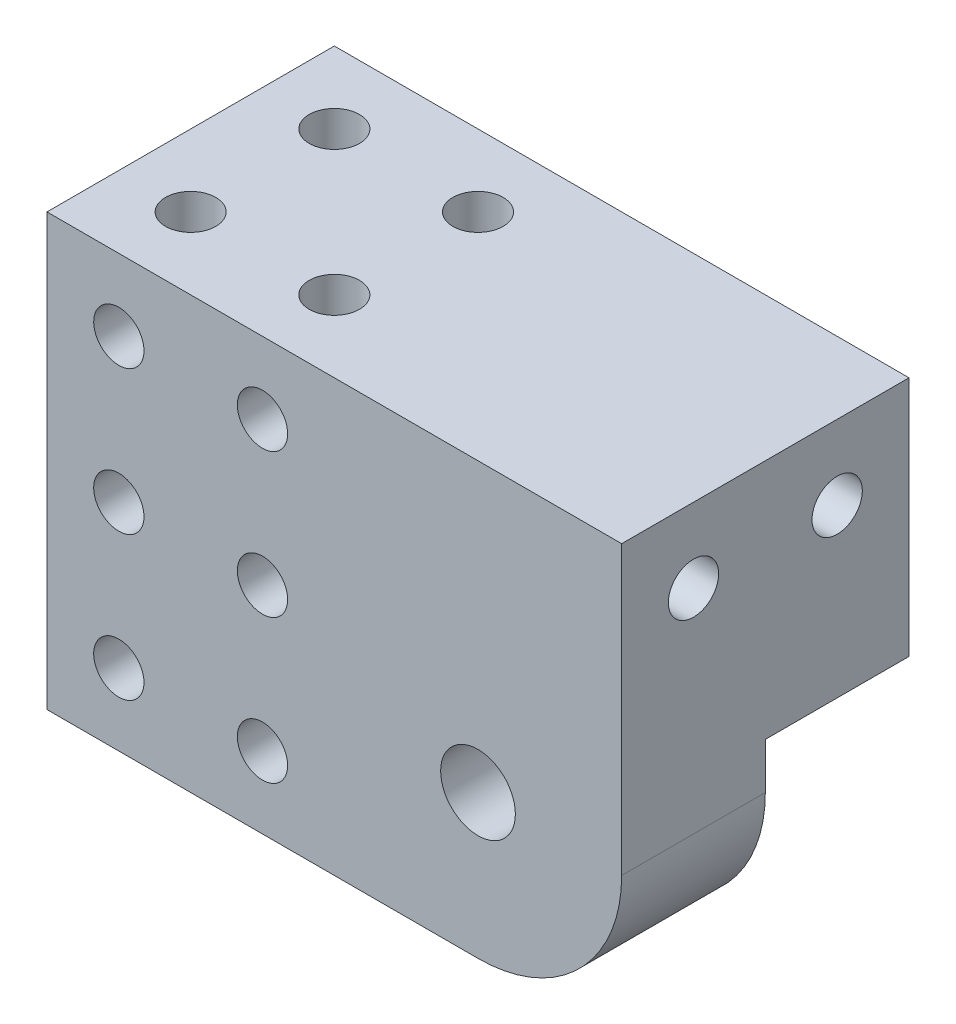
SolidWorks part; units mm, degrees
ref_plane "Plan de face" through (0, 0, 0) normal (0, 0, 1) x (1, 0, 0)
ref_plane "Plan de dessus" through (0, 0, 0) normal (0, 1, 0) x (1, 0, 0)
ref_plane "Plan de droite" through (0, 0, 0) normal (1, 0, 0) x (0, 0, -1)
sketch "Esquisse1" plane through (0, 0, 0) normal (0, 0, 1) x (1, 0, 0)
  line L0 (0, 0) -> (0, 30)
  line L1 (0, 30) -> (30, 30)
  line L2 (30, 30) -> (30, 0) construction
  line L3 (5, 30) -> (5, 0) construction
  line L4 (30, 0) -> (0, 0)
  line L5 (15, 30) -> (15, 0) construction
  line L6 (30, 30) -> (30, 0) construction
  line L7 (40, 10) -> (40, 30)
  line L8 (40, 30) -> (30, 30)
  circle A0 centre (5, 5) radius 1.75
  circle A1 centre (5, 25) radius 1.75
  circle A2 centre (5, 15) radius 1.75
  circle A3 centre (15, 15) radius 1.75
  circle A4 centre (15, 25) radius 1.75
  circle A5 centre (15, 5) radius 1.75
  arc A6 (30, 0) -> (40, 10) centre (30, 10) ccw
  circle A7 centre (30, 10) radius 2.6
  point P19 (15, 30)
  dimension "D7" = 3.5
  dimension "D13" = 5.2
  dimension "D12" = 10
  dimension "D1" = 30
  dimension "D2" = 30
  dimension "D3" = 5
  dimension "D4" = 10
  dimension "D5" = 10
  dimension "D6" = 5
  dimension "D8" = 5
  dimension "D9" = 10
  dimension "D10" = 10
  dimension "D11" = 10
  dimension "D14" = 10
extrude "Boss.-Extru.1" add sketch "Esquisse1" along normal blind 20
sketch "Esquisse2" plane through (0, 0, 0) normal (0, -1, 0) x (-1, 0, 0)
  line L0 (-5, -20) -> (-5, 0) construction
  line L1 (0, -20) -> (-30, -20) construction
  line L2 (0, 0) -> (-30, 0) construction
  line L3 (-15, -20) -> (-15, 0) construction
  line L4 (0, -20) -> (0, 0) construction
  circle A0 centre (-5, -15) radius 1.75
  circle A1 centre (-5, -5) radius 1.75
  circle A2 centre (-15, -5) radius 1.75
  circle A3 centre (-15, -15) radius 1.75
  dimension "D1" = 3.5
  dimension "D2" = 5
  dimension "D3" = 10
  dimension "D4" = 5
  dimension "D5" = 10
  dimension "D6" = 5
  dimension "D7" = 10
extrude "Enlèv. mat.-Extru.1" cut sketch "Esquisse2" against normal through all
sketch "Esquisse3" plane through (0, 0, 0) normal (0, 0, -1) x (-1, 0, 0)
  circle A0 centre (-30, 10) radius 10.5
  circle A1 centre (-30, 10) radius 2.6 construction
  dimension "D1" = 21
extrude "Enlèv. mat.-Extru.2" cut sketch "Esquisse3" against normal blind 10
sketch "Esquisse4" plane through (0, 0, 0) normal (-1, 0, 0) x (0, 0, 1)
  line L0 (20, 24.818) -> (0, 24.818) construction
  line L1 (20, 30) -> (20, 0) construction
  line L2 (0, 30) -> (0, 0) construction
  line L3 (0, 11.1726) -> (20, 11.1726) construction
  circle A0 centre (15, 24.818) radius 1.75
  circle A1 centre (5, 24.818) radius 1.75
  dimension "D1" = 3.5
  dimension "D2" = 10
  dimension "D3" = 5
extrude "Enlèv. mat.-Extru.3" cut sketch "Esquisse4" against normal through all
chamfer "Chanfrein1" distance 1.5 angle 45 1 edges at (27.4, 10, 10)
